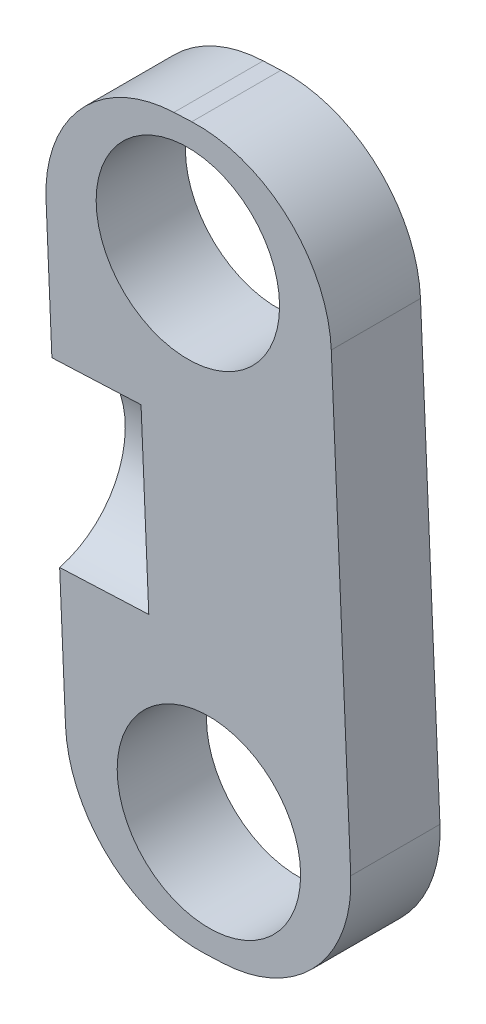
SolidWorks part; units mm, degrees
material "ABS"
ref_plane "Front Plane" through (0, 0, 0) normal (0, 0, 1) x (1, 0, 0)
ref_plane "Top Plane" through (0, 0, 0) normal (0, 1, 0) x (1, 0, 0)
ref_plane "Right Plane" through (0, 0, 0) normal (1, 0, 0) x (0, 0, -1)
sketch "Sketch1" plane through (0, 0, 0) normal (0, 0, 1) x (1, 0, 0)
  line L0 (0, 0) -> (196.85, 0) construction
  line L1 (0, 0) -> (196.1009, 17.1566) construction
  line L2 (196.1009, 17.1566) -> (196.85, 0) construction
  line L3 (196.4755, 8.5783) -> (200.9967, 21.4878) construction
  line L4 (200.9967, 21.4878) -> (196.4755, 8.5783) construction
  line L5 (196.4755, 8.5783) -> (191.9543, -4.3312) construction
  line L6 (200.9967, 21.4878) -> (190.8463, 21.0446)
  line L7 (190.8463, 21.0446) -> (196.4755, 8.5783) construction
  line L8 (196.4755, 8.5783) -> (202.1046, -3.888) construction
  line L9 (191.9543, -4.3312) -> (202.1046, -3.888)
  line L10 (191.9543, -4.3312) -> (190.8463, 21.0446)
  line L11 (200.9967, 21.4878) -> (202.1046, -3.888)
  circle A0 centre (196.85, 0) radius 3.2639
  circle A1 centre (196.1009, 17.1566) radius 3.2639
  dimension "D2" = 6.5278
  dimension "D5" = 6.5278
  dimension "D1" = 196.85
  dimension "D3" = 5
  dimension "D4" = 196.85
  dimension "D6" = 10.16
  dimension "D7" = 25.4
extrude "Boss-Extrude1" add sketch "Sketch1" along normal blind 3.175
fillet "Fillet1" radius 4.7625 4 edges at (202.1046, -3.888, 1.5875) (191.9543, -4.3312, 1.5875) (200.9967, 21.4878, 1.5875) (190.8463, 21.0446, 1.5875)
sketch "Sketch2" plane through (191.4003, 8.3567, 0) normal (-0.999, -0.0436, 0) x (0, 0, 1)
  line L0 (0, 0) -> (3.9688, 0) construction
  line L1 (0, 7.9375) -> (0, -7.9375) construction
  circle A0 centre (3.9688, 0) radius 3.2639
  point P5 (1.7681, 0)
  dimension "D2" = 6.5278
  dimension "D1" = 3.9688
extrude "Cut-Extrude1" cut sketch "Sketch2" against normal blind 3.175
